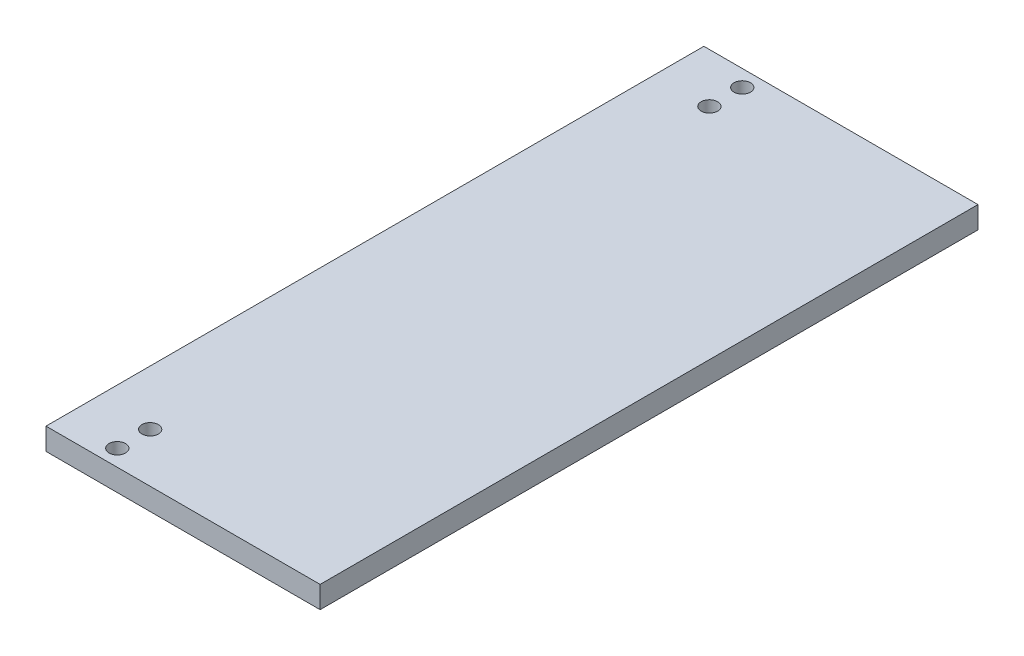
SolidWorks part; units mm, degrees
material "Custom Plastic"
ref_plane "Front Plane" through (0, 0, 0) normal (0, 0, 1) x (1, 0, 0)
ref_plane "Top Plane" through (0, 0, 0) normal (0, 1, 0) x (1, 0, 0)
ref_plane "Right Plane" through (0, 0, 0) normal (1, 0, 0) x (0, 0, -1)
sketch "Sketch1" plane through (0, 0, 0) normal (0, 1, 0) x (1, 0, 0)
  line L1 (-25, 60) -> (25, 60)
  line L2 (-25, 60) -> (-25, -60)
  line L3 (-25, -60) -> (25, -60)
  line L4 (25, 60) -> (25, -60)
  line L5 (-25, 60) -> (25, -60) construction
  line L6 (-25, -60) -> (25, 60) construction
  point P0 (0, 0)
  dimension "D1" = 50
  dimension "D2" = 120
extrude "Boss-Extrude1" add sketch "Sketch1" along normal blind 4
sketch "Sketch2" plane through (0, 0, 0) normal (0, -1, 0) x (1, 0, 0)
  circle A0 centre (-15, -57) radius 1.5
  circle A1 centre (-15, -51) radius 1.5
  circle A2 centre (-15, 51) radius 1.5
  circle A3 centre (-15, 57) radius 1.5
  dimension "D1" = 3
extrude "Cut-Extrude1" cut sketch "Sketch2" against normal through all
